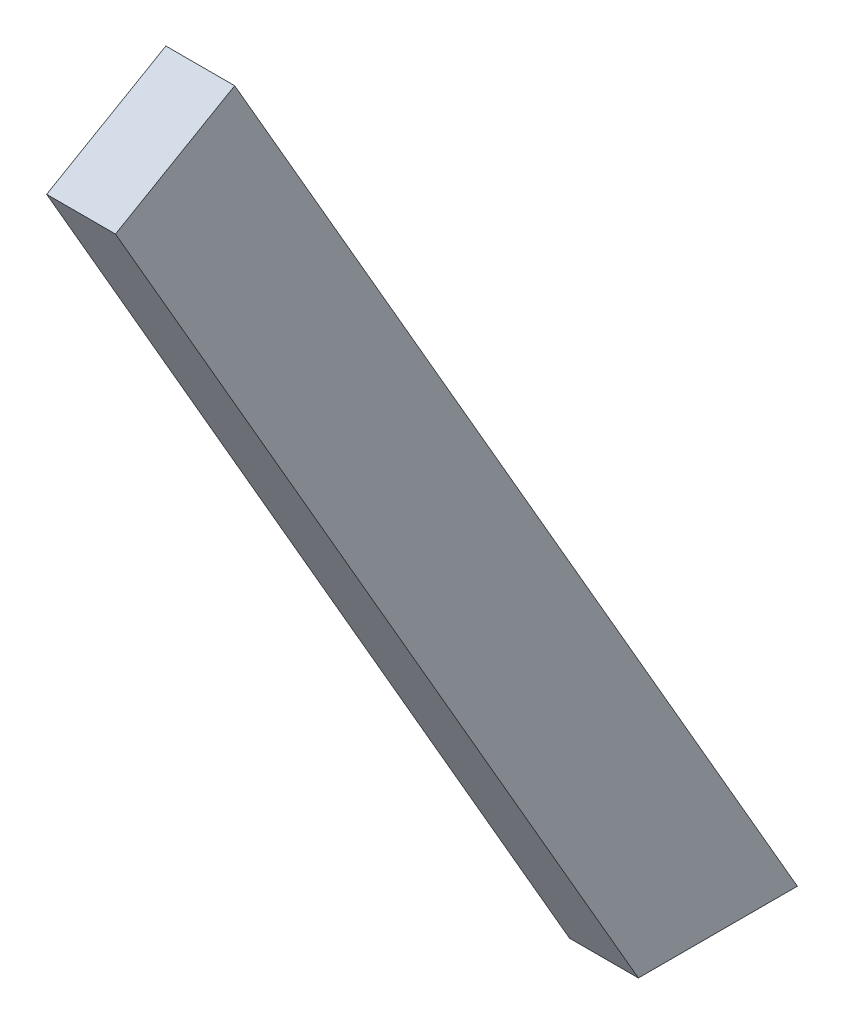
SolidWorks part; units mm, degrees
ref_plane "Front Plane" through (0, 0, 0) normal (0, 0, 1) x (1, 0, 0)
ref_plane "Top Plane" through (0, 0, 0) normal (0, 1, 0) x (1, 0, 0)
ref_plane "Right Plane" through (0, 0, 0) normal (1, 0, 0) x (0, 0, -1)
sketch "Sketch2" plane through (0, 0, 0) normal (1, 0, 0) x (0, 0, -1)
  line L0 (0, 0) -> (-192.985, 334.2598)
  line L1 (-192.985, 334.2598) -> (-148.9909, 359.6598)
  line L2 (-148.9909, 359.6598) -> (58.6588, 0)
  line L3 (58.6588, 0) -> (0, 0)
  line L4 (0, 0) -> (43.9941, 25.4) construction
  line L5 (0, 0) -> (-8.7538, 0) construction
  line L6 (-148.9909, 359.6598) -> (-153.2453, 352.291) construction
  line L7 (-148.9909, 359.6598) -> (-148.9909, 0) construction
  line L8 (-148.9909, 0) -> (58.6588, 0) construction
  dimension "D1" = 50.8
  dimension "D2" = 359.6598
  dimension "D3" = 60
  dimension "D4" = 60
extrude "Boss-Extrude1" add sketch "Sketch2" along normal blind 25.4
